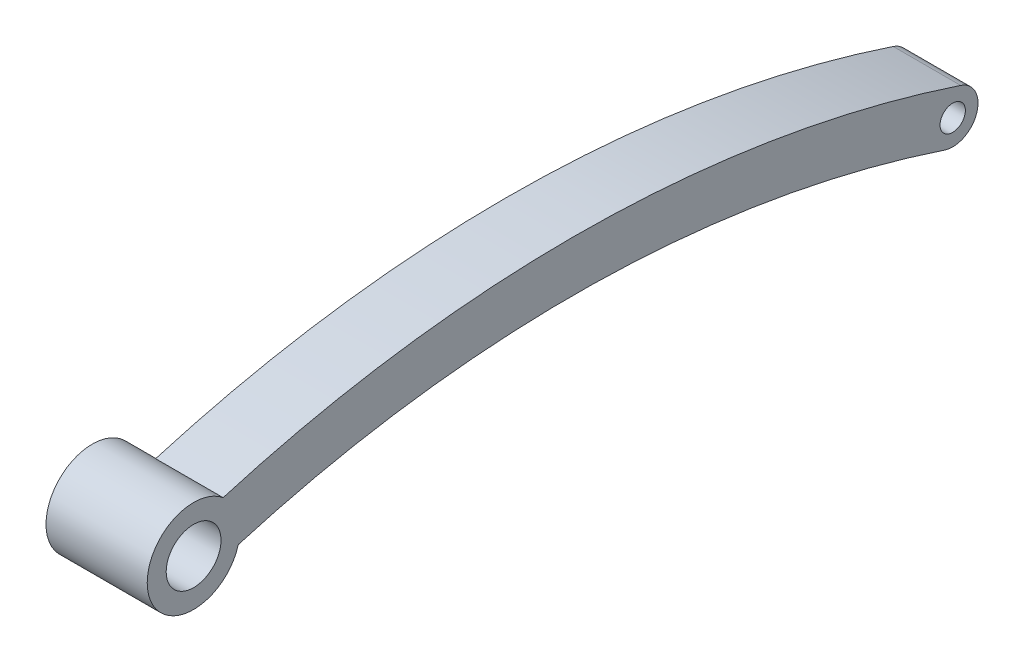
SolidWorks part; units mm, degrees
ref_plane "Front Plane" through (0, 0, 0) normal (0, 0, 1) x (1, 0, 0)
ref_plane "Top Plane" through (0, 0, 0) normal (0, 1, 0) x (1, 0, 0)
ref_plane "Right Plane" through (0, 0, 0) normal (1, 0, 0) x (0, 0, -1)
sketch "Sketch1" plane through (0, 0, 0) normal (1, 0, 0) x (0, 0, -1)
  line L0 (0, 0) -> (45, 0) construction
  arc A0 (-0.472, 1.4238) -> (0.472, -1.4238) centre (0, 0) ccw
  arc A1 (44.528, -1.4238) -> (45.472, 1.4238) centre (45, 0) ccw
  circle A2 centre (45, 0) radius 0.75
  circle A3 centre (0, 0) radius 1.625 construction
  arc A4 (-0.472, 1.4238) -> (45.472, 1.4238) centre (22.5, -67.8675) cw
  arc A5 (0.472, -1.4238) -> (44.528, -1.4238) centre (22.5, -67.8675) cw
  dimension "D2" = 3
  dimension "D3" = 3.25
  dimension "D4" = 70
  dimension "D5" = 1.5
  dimension "D1" = 45
extrude "Boss-Extrude1" add sketch "Sketch1" along normal blind 4
sketch "Sketch3" plane through (0, 0, 0) normal (-1, 0, 0) x (0, 0, 1)
  circle A0 centre (0, 0) radius 2.75
  dimension "D1" = 5.5
extrude "Boss-Extrude3" add sketch "Sketch3" against normal blind 4
sketch "Sketch4" plane through (0, 0, 0) normal (-1, 0, 0) x (0, 0, 1)
  circle A0 centre (0, 0) radius 1.625
  dimension "D1" = 3.25
extrude "Cut-Extrude1" cut sketch "Sketch4" against normal blind 4
sketch "Sketch5" plane through (0, 0, 0) normal (-1, 0, 0) x (0, 0, 1)
  circle A0 centre (0, 0) radius 1.625
  circle A1 centre (0, 0) radius 2.75
extrude "Boss-Extrude4" add sketch "Sketch5" along normal blind 2
